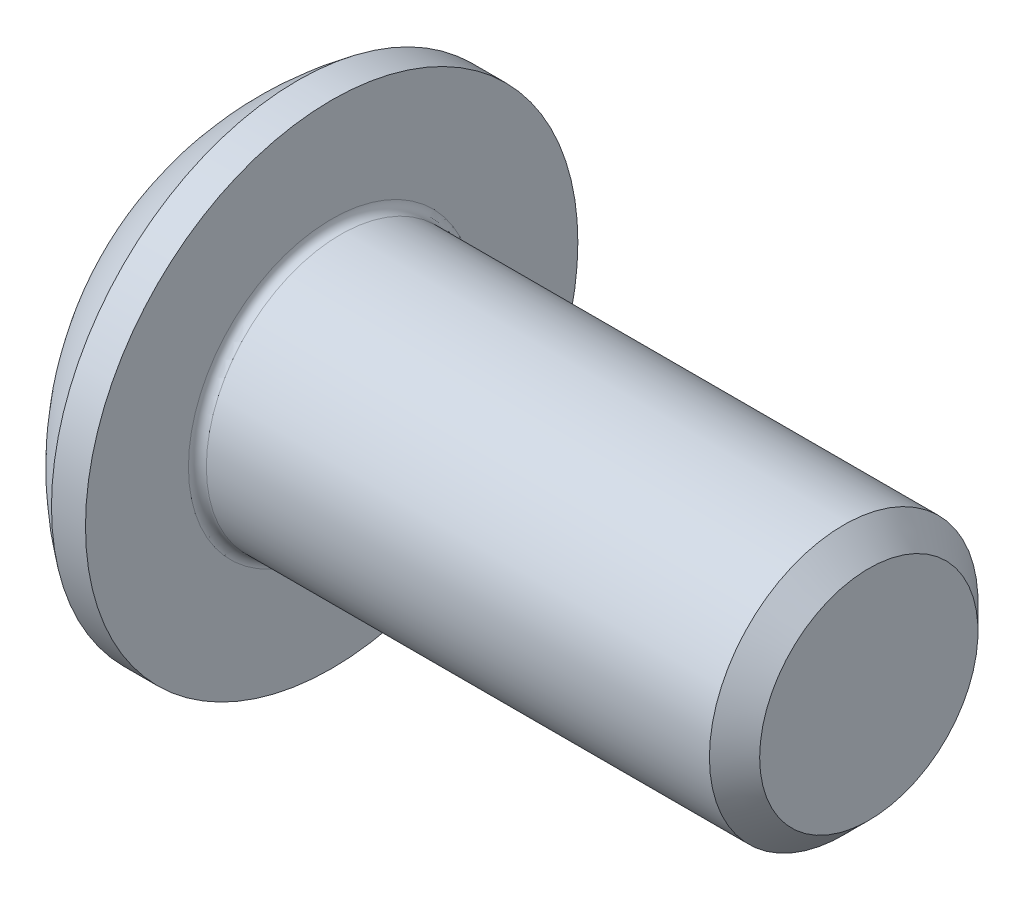
SolidWorks part; units mm, degrees
ref_plane "Plane1" through (0, 0, 0) normal (0, 0, 1) x (1, 0, 0)
ref_plane "Plane2" through (0, 0, 0) normal (0, 1, 0) x (1, 0, 0)
ref_plane "Plane3" through (0, 0, 0) normal (1, 0, 0) x (0, 0, -1)
sketch "BodySke" plane through (0, 0, 0) normal (0, 0, 1) x (1, 0, 0)
  line L0 (7.5, 0) -> (7.5, 1.2195)
  line L1 (7.2195, 1.5) -> (1.5, 1.5)
  line L2 (1.5, 1.5) -> (1.5, 2.75)
  line L3 (1.5, 2.75) -> (1.12, 2.75)
  line L4 (0, 0) -> (101.6, 0) construction
  line L5 (1.5, -2.75) -> (1.12, -2.75) construction
  line L6 (55.6768, -1.5) -> (1.5, -1.5) construction
  line L7 (7.5, 0) -> (0, 0)
  line L8 (0, 1.375) -> (0, -1.375) construction
  line L9 (0, 0) -> (0, 1.375)
  line L10 (7.5, 1.2195) -> (7.2195, 1.5)
  line L11 (7.5, -1.2195) -> (7.2195, -1.5) construction
  line L12 (2, 9.525) -> (2, -1.5) construction
  line L13 (1.5, 9.525) -> (1.5, -1.5) construction
  arc A1 (0, 1.375) -> (1.12, 2.75) centre (3.0921, 0) cw
  dimension "D1" = 2.75
  dimension "Diameter" = 3
  dimension "Length" = 6
  dimension "Head_dia" = 5.5
  dimension "Head_ht" = 1.5
  dimension "Head_side_ht" = 0.38
  dimension "Minor_dia" = 2.439
  dimension "Body_ch_ang" = 45
  dimension "Advance" = 0.5
  dimension "Thread_nom" = 6
revolve "BaseBody" add sketch "BodySke" angle 360 about L4
cosmetic thread "ThreadCosmetic" parameters "Thread_length"=5, "Thread_minor"=2.439
fillet "Fillet1" radius 0.1 1 edges at (1.5, 0, 1.5)
sketch "Sketch2" plane through (0, 0, 0) normal (0, 0, 1) x (1, 0, 0)
  line L0 (0, 1) -> (1.04, 1)
  line L1 (1.04, 1) -> (1.6174, 0)
  line L3 (1.6174, 0) -> (0, 0)
  line L4 (0, 0) -> (0, 1)
  line L5 (0, -1) -> (1.04, -1) construction
  line L6 (0, 0) -> (47.625, 0) construction
  dimension "D2" = 60
  dimension "PreBroach_depth" = 1.04
  dimension "PreBroach_dia" = 2
revolve "PreBroach" cut sketch "Sketch2" angle 360 about L6
sketch "Sketch3" plane through (0, 0, 0) normal (1, 0, 0) x (0, 0, -1)
  line L0 (-1, -0.5774) -> (-1, 0.5774)
  line L1 (-1, 0.5774) -> (0, 1.1547)
  line L2 (0, 1.1547) -> (1, 0.5774)
  line L3 (1, 0.5774) -> (1, -0.5774)
  line L4 (1, -0.5774) -> (0, -1.1547)
  line L5 (0, -1.1547) -> (-1, -0.5774)
  dimension "D1" = 1
  dimension "D2" = 1
  dimension "D3" = 2
  dimension "Hex_size" = 2
extrude "Hex" cut sketch "Sketch3" along normal blind 1.04
sketch "ThdSchSke" plane through (0, 0, 0) normal (0, 0, 1) x (1, 0, 0)
  line L0 (2.5, -1.2195) -> (2.3036, -1.5)
  line L1 (2.5, -1.2195) -> (2.6964, -1.5)
  line L2 (2.6964, -1.5) -> (2.6964, -1.875)
  line L3 (-3.175, 0) -> (5.1513, 0) construction
  line L5 (2.6964, -1.875) -> (2.3036, -1.875)
  line L6 (2.3036, -1.875) -> (2.3036, -1.5)
  dimension "Thread_minor" = 2.439
  dimension "Diameter" = 3
  dimension "Start" = 2.5
  dimension "SideAngle" = 55
  dimension "VeeAngle" = 70
  dimension "Overcut" = 3.75
revolve "ThreadSchematic" [suppressed] cut sketch "ThdSchSke" angle 360 about L3
pattern_linear "ThdSchPat" [suppressed]
equation "\"D1@BodySke\" = \"Head_dia@BodySke\" * .5"
equation "\"Thread_minor@ThreadCosmetic\" = \"Minor_dia@BodySke\""
equation "\"D1@Sketch3\" = \"Hex_size@Sketch3\" / 2"
equation "\"D2@Sketch3\" = \"D1@Sketch3\""
equation "\"D3@Sketch3\" = \"Hex_size@Sketch3\""
equation "\"Thread_length@ThreadCosmetic\" = ((sgn( (\"Length@BodySke\" - \"Advance@BodySke\" * 2.0) - \"Thread_nom@BodySke\" )-1)*( (\"Length@BodySke\" - \"Advance@BodySke\" * 2.0) - \"Thread_nom@BodySke\" ))/-2+ \"Thread_nom@BodySke\""
equation "\"Thread_minor@ThdSchSke\" = \"Minor_dia@BodySke\""
equation "\"Diameter@ThdSchSke\" = \"Diameter@BodySke\""
equation "\"Overcut@ThdSchSke\" = \"Diameter@BodySke\" * 1.25"
equation "\"Start@ThdSchSke\" = \"Head_ht@BodySke\" + \"Length@BodySke\" - \"Thread_length@ThreadCosmetic\"  '---Non-countersunk---"
equation "\"Num_threads@ThdSchPat\" = int( \"Thread_length@ThreadCosmetic\" / \"Advance@BodySke\" + 0.999 )  + 1"
equation "\"Advance@ThdSchPat\" = \"Thread_length@ThreadCosmetic\" /  (\"Num_threads@ThdSchPat\" - 1) 'relax it"
equation "\"Num_threads@ThdSchPat\" = \"Num_threads@ThdSchPat\" - sgn( \"Num_threads@ThdSchPat\" - 1) '---chamfered tips only---"
